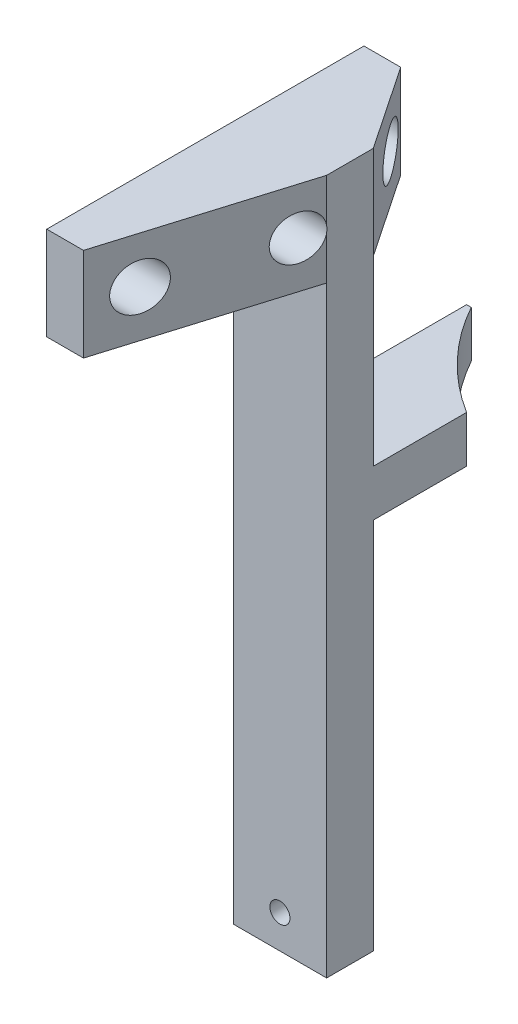
SolidWorks part; units mm, degrees
ref_plane "前视基准面" through (0, 0, 0) normal (0, 0, 1) x (1, 0, 0)
ref_plane "上视基准面" through (0, 0, 0) normal (0, 1, 0) x (1, 0, 0)
ref_plane "右视基准面" through (0, 0, 0) normal (1, 0, 0) x (0, 0, -1)
sketch "草图1" plane through (0, 0, 0) normal (0, 0, 1) x (1, 0, 0)
  line L0 (20.0138, -131.8034) -> (20.0138, 17.2116) construction
  line L7 (10.0138, 17.2116) -> (30.0138, 17.2116)
  line L8 (10.0138, 17.2116) -> (10.0138, -131.8034)
  line L9 (10.0138, -131.8034) -> (30.0138, -131.8034)
  line L10 (30.0138, 17.2116) -> (30.0138, -131.8034)
  circle A0 centre (20, -124.6534) radius 2.15
  dimension "D1" = 4.3
  dimension "D4" = 149.015
  dimension "D5" = 7.15
  dimension "D6" = 20
extrude "凸台-拉伸1" add sketch "草图1" along normal blind 10
sketch "草图2" plane through (0, 0, 10) normal (0, 0, 1) x (1, 0, 0)
  line L0 (30.0138, -131.8034) -> (30.0138, 17.2116) construction
  line L1 (10.0138, 17.2116) -> (30.0138, 17.2116)
  line L2 (10.0138, 17.2116) -> (10.0138, -2.7884)
  line L3 (10.0138, -2.7884) -> (30.0138, -2.7884)
  line L4 (30.0138, 17.2116) -> (30.0138, -2.7884)
  dimension "D1" = 20
extrude "凸台-拉伸2" add sketch "草图2" along normal blind 40
sketch "草图3" plane through (0, 0, 0) normal (0, 0, -1) x (-1, 0, 0)
  line L0 (-10.0138, 17.2116) -> (-10.0138, -131.8034) construction
  line L1 (-30.0138, 17.2116) -> (-10.0138, 17.2116)
  line L2 (-30.0138, 17.2116) -> (-30.0138, -2.7884)
  line L3 (-30.0138, -2.7884) -> (-10.0138, -2.7884)
  line L4 (-10.0138, 17.2116) -> (-10.0138, -2.7884)
  dimension "D1" = 20
extrude "凸台-拉伸3" add sketch "草图3" along normal blind 18
sketch "草图4" plane through (0, -2.7884, 0) normal (0, -1, 0) x (1, 0, 0)
  line L0 (17.8938, 50) -> (30.0138, 50)
  line L1 (10.0138, 50) -> (30.0138, 50) construction
  line L2 (30.0138, 50) -> (30.0138, 10)
  line L3 (30.0138, 10) -> (17.8938, 50)
  line L4 (10.0138, 50) -> (10.0138, 10) construction
  line L5 (17.8938, -18) -> (30.0138, -18)
  line L6 (30.0138, -18) -> (10.0138, -18) construction
  line L7 (30.0138, -18) -> (30.0138, 0)
  line L8 (30.0138, 0) -> (17.8938, -18)
  line L9 (10.0138, -18) -> (10.0138, 0) construction
  dimension "D1" = 7.88
  dimension "D2" = 7.88
extrude "切除-拉伸1" cut sketch "草图4" against normal blind 20 and the other way blind 10
sketch "草图5" plane through (10.0138, 0, 0) normal (-1, 0, 0) x (0, 0, 1)
  line L0 (10, -49.2013) -> (10, 38.8132) construction
  line L1 (10, -2.7884) -> (10, -131.8034) construction
  line L2 (50, 7.2116) -> (-18, 7.2116) construction
  line L3 (50, 17.2116) -> (50, -2.7884) construction
  line L4 (-18, -2.7884) -> (-18, 17.2116) construction
  circle A0 centre (14.7, 7.2116) radius 2.2
  circle A2 centre (40.7, 7.2116) radius 2.2
  circle A3 centre (-11.3, 7.2116) radius 2.2
  dimension "D1" = 4.4
  dimension "D7" = 4.4
  dimension "D8" = 4.4
  dimension "D6" = 4.7
  dimension "D9" = 26
  dimension "D10" = 26
extrude "切除-拉伸2" cut sketch "草图5" against normal blind 2
sketch "草图6" plane through (10.0138, 0, 0) normal (-1, 0, 0) x (0, 0, 1)
  circle A2 centre (40.7, 7.2116) radius 5
  circle A3 centre (-11.3, 7.2116) radius 5
  circle A4 centre (14.7, 7.2116) radius 4.75
  dimension "D1" = 10
  dimension "D2" = 9.5
  dimension "D4" = 10
extrude "切除-拉伸3" cut sketch "草图6" against normal blind 20 from offset 2 offset against normal yes
sketch "草图7" plane through (0, 0, 0) normal (0, 0, -1) x (-1, 0, 0)
  line L0 (-30.0138, -131.8034) -> (-30.0138, -2.7884) construction
  line L1 (-30.0138, -41.8034) -> (-10.0138, -41.8034)
  line L2 (-30.0138, -41.8034) -> (-30.0138, -51.8034)
  line L3 (-30.0138, -51.8034) -> (-10.0138, -51.8034)
  line L4 (-10.0138, -41.8034) -> (-10.0138, -51.8034)
  line L5 (-10.0138, -2.7884) -> (-10.0138, -131.8034) construction
  line L6 (-10.0138, -131.8034) -> (-30.0138, -131.8034) construction
  dimension "D1" = 80
  dimension "D2" = 10
extrude "凸台-拉伸4" add sketch "草图7" along normal blind 40
sketch "草图8" plane through (0, -41.8034, 0) normal (0, 1, 0) x (1, 0, 0)
  line L2 (30.0138, 40) -> (30.0138, 0) construction
  line L3 (10.0138, 40) -> (30.0138, 40) construction
  line L4 (30.0138, 20) -> (30.0138, 40)
  line L5 (30.0138, 40) -> (11.0138, 40)
  arc A0 (11.0138, 40) -> (30.0138, 20) centre (59.1145, 66.6707) ccw
  dimension "D1" = 110
  dimension "D2" = 20
  dimension "D3" = 19
extrude "切除-拉伸5" cut sketch "草图8" against normal up to next
